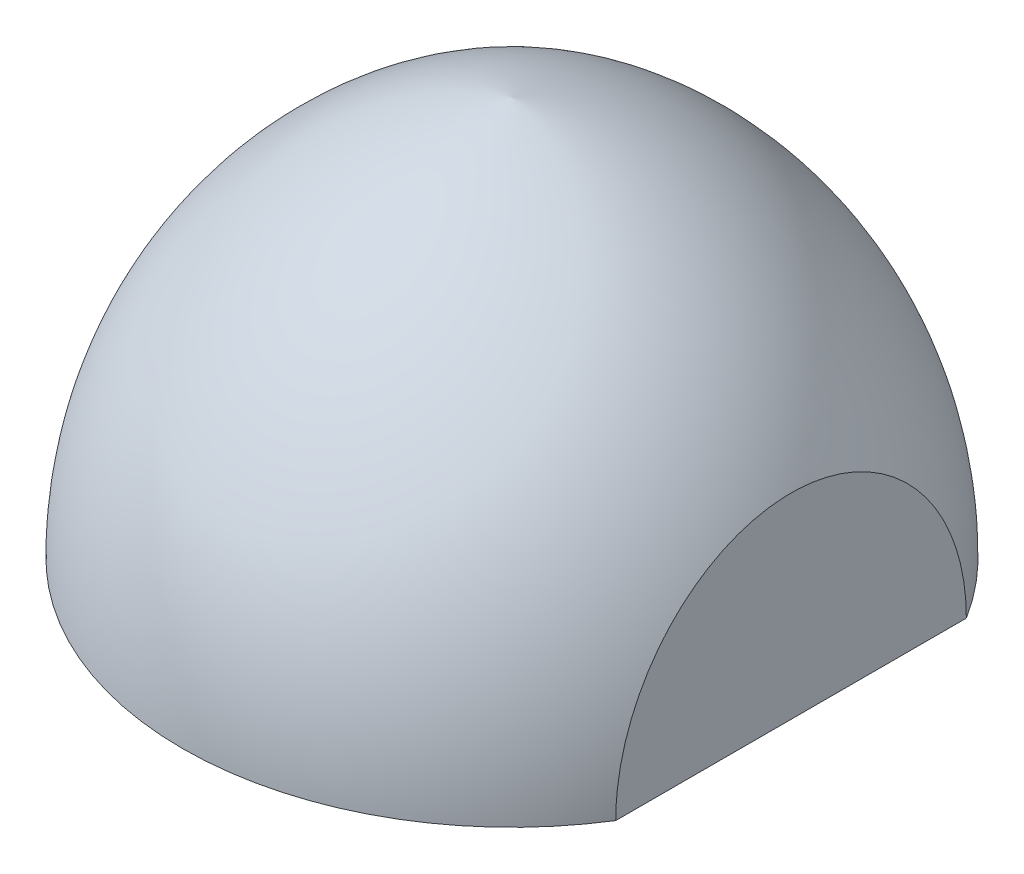
SolidWorks part; units mm, degrees
ref_plane "Front Plane" through (0, 0, 0) normal (0, 0, 1) x (1, 0, 0)
ref_plane "Top Plane" through (0, 0, 0) normal (0, 1, 0) x (1, 0, 0)
ref_plane "Right Plane" through (0, 0, 0) normal (1, 0, 0) x (0, 0, -1)
sketch "Sketch1" plane through (0, 0, 0) normal (0, 0, 1) x (1, 0, 0)
  line L0 (62, 0) -> (59, 0)
  line L2 (0, 75) -> (0, 71.9432)
  arc A0 (62, 0) -> (0, 75) centre (-14.3629, 0) ccw
  arc A1 (59, 0) -> (0, 71.9432) centre (-14.3629, 0) ccw
  arc A2 (59, 0) -> (-0.5643, 72.0535) centre (-14.3629, 0) ccw construction
  dimension "D1" = 3
  dimension "D2" = 62
  dimension "D3" = 75
revolve "Revolve1" add sketch "Sketch1" angle 360 about L2
sketch "Sketch2" plane through (0, 0, 0) normal (0, -1, 0) x (-1, 0, 0)
  line L1 (52.5, 72.8837) -> (-52.5, 72.8837)
  line L2 (52.5, 72.8837) -> (52.5, -72.8837)
  line L3 (52.5, -72.8837) -> (-52.5, -72.8837)
  line L4 (-52.5, 72.8837) -> (-52.5, -72.8837)
  line L5 (52.5, 72.8837) -> (-52.5, -72.8837) construction
  line L6 (52.5, -72.8837) -> (-52.5, 72.8837) construction
  point P0 (0, 0)
  dimension "D1" = 105
  dimension "D2" = 145.7674
extrude "Cut-Extrude2" cut sketch "Sketch2" against normal through all flip side to cut
sketch "Sketch3" plane through (0, 0, 0) normal (0, -1, 0) x (1, 0, 0)
  line L0 (-52.5, 32.9811) -> (-48.9209, 32.9811)
  line L1 (-48.9209, 32.9811) -> (-48.9209, -32.9811)
  line L2 (-48.9209, -32.9811) -> (-52.5, -32.9811)
  line L3 (-52.5, -32.9811) -> (-52.5, 32.9811)
  line L4 (0, 0) -> (0, 17.4115) construction
  line L5 (48.9209, -32.9811) -> (52.5, -32.9811)
  line L6 (52.5, 32.9811) -> (48.9209, 32.9811)
  line L7 (52.5, -32.9811) -> (52.5, 32.9811)
  line L8 (48.9209, 32.9811) -> (48.9209, -32.9811)
  arc A0 (52.5, 26.9212) -> (-52.5, 26.9212) centre (0, 0) ccw construction
  arc A1 (-52.5, -26.9212) -> (52.5, -26.9212) centre (0, 0) ccw construction
extrude "Boss-Extrude2" add sketch "Sketch3" against normal up to surface
